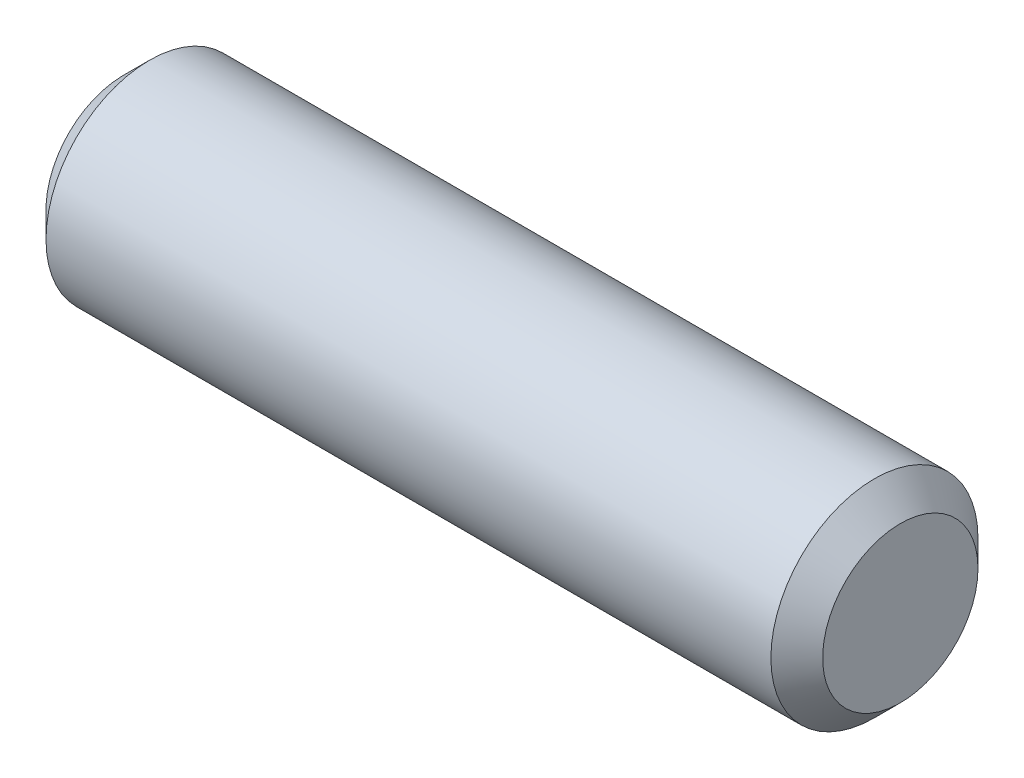
SolidWorks part; units mm, degrees
ref_plane "Piano frontale" through (0, 0, 0) normal (0, 0, 1) x (1, 0, 0)
ref_plane "Piano superiore" through (0, 0, 0) normal (0, 1, 0) x (1, 0, 0)
ref_plane "Piano destro" through (0, 0, 0) normal (1, 0, 0) x (0, 0, -1)
sketch "Schizzo2" plane through (0, 0, 0) normal (1, 0, 0) x (0, 0, -1)
  circle A0 centre (0, 0) radius 4
  dimension "D1" = 8
extrude "Estrusione-Estrusione1" add sketch "Schizzo2" along normal mid plane 30
chamfer "Smusso1" distance 1 angle 45 2 edges at (-15, 0, -4) (15, 0, -4)
